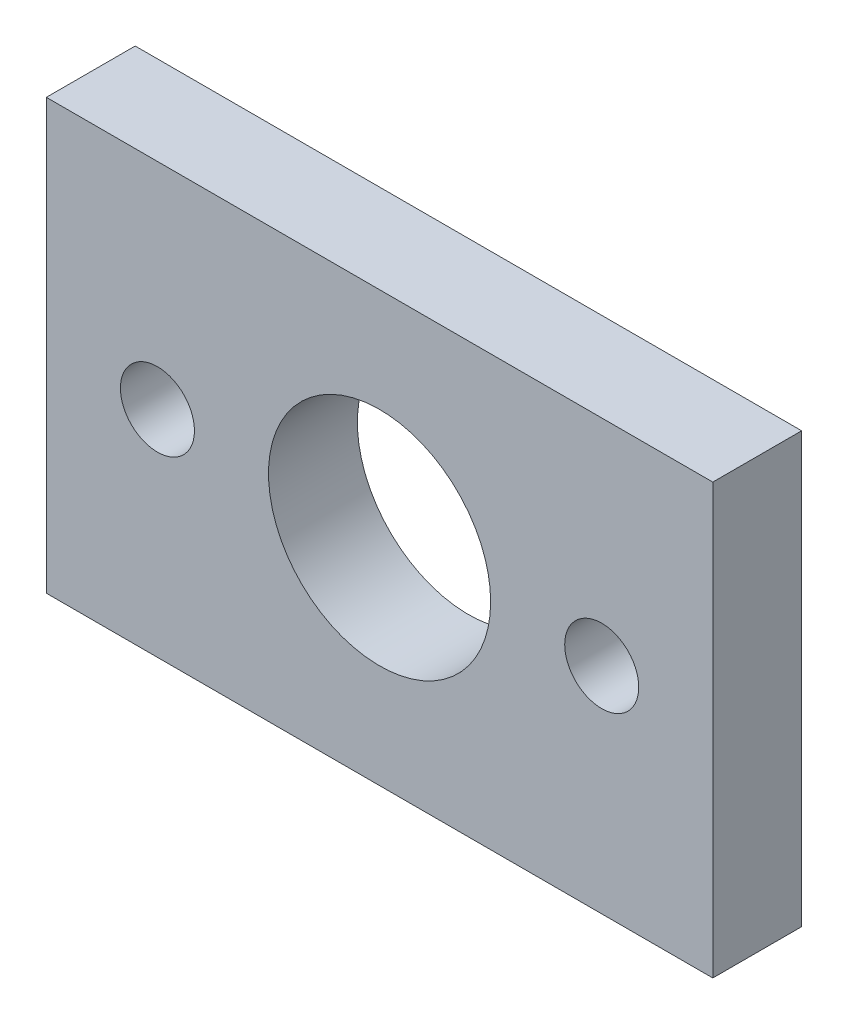
SolidWorks part; units mm, degrees
ref_plane "Front Plane" through (0, 0, 0) normal (0, 0, 1) x (1, 0, 0)
ref_plane "Top Plane" through (0, 0, 0) normal (0, 1, 0) x (1, 0, 0)
ref_plane "Right Plane" through (0, 0, 0) normal (1, 0, 0) x (0, 0, -1)
sketch "Sketch1" plane through (0, 0, 0) normal (0, 0, 1) x (1, 0, 0)
  line L0 (0, 29) -> (45, 0) construction
  line L1 (0, 0) -> (45, 0)
  line L2 (0, 0) -> (0, 29)
  line L3 (0, 29) -> (45, 29)
  line L4 (45, 0) -> (45, 29)
  line L5 (22.5, 14.5) -> (22.5, 0) construction
  line L6 (22.5, 14.5) -> (0, 14.5) construction
  line L7 (22.5, 14.5) -> (22.5, 29) construction
  circle A0 centre (22.5, 14.5) radius 7.5
  circle A1 centre (7.5, 14.5) radius 2.5
  circle A2 centre (37.5, 14.5) radius 2.5
  dimension "D1" = 15
  dimension "D4" = 5
  dimension "D2" = 45
  dimension "D3" = 14.5
  dimension "D5" = 7.5
extrude "Boss-Extrude1" add sketch "Sketch1" along normal blind 6
